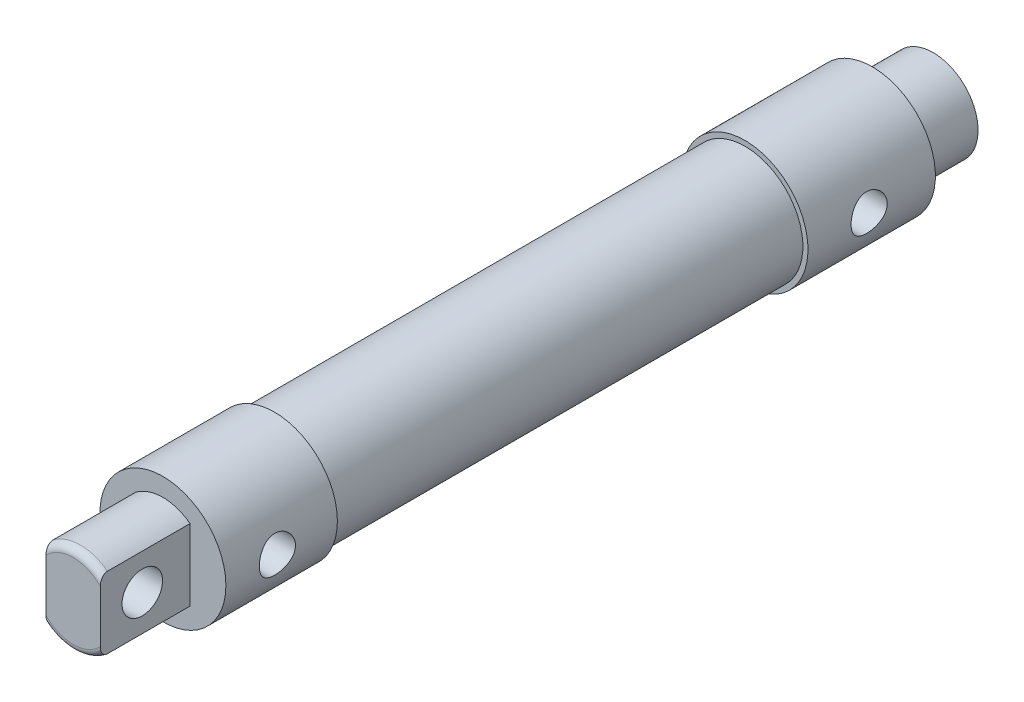
SolidWorks part; units mm, degrees
ref_plane "Front Plane" through (0, 0, 0) normal (0, 0, 1) x (1, 0, 0)
ref_plane "Top Plane" through (0, 0, 0) normal (0, 1, 0) x (1, 0, 0)
ref_plane "Right Plane" through (0, 0, 0) normal (1, 0, 0) x (0, 0, -1)
sketch "Sketch1" plane through (0, 0, 0) normal (0, 0, 1) x (1, 0, 0)
  circle A0 centre (0, 0) radius 10.16
  dimension "D1" = 20.32
extrude "Boss-Extrude1" add sketch "Sketch1" along normal blind 82.55
sketch "Sketch2" plane through (0, 0, 82.55) normal (0, 0, 1) x (1, 0, 0)
  circle A0 centre (0, 0) radius 11.049
  dimension "D1" = 22.098
extrude "Boss-Extrude2" add sketch "Sketch2" along normal blind 19.558 separate body
sketch "Sketch3" plane through (0, 0, 102.108) normal (0, 0, 1) x (1, 0, 0)
  line L0 (0, -7.874) -> (0, 7.874) construction
  line L1 (4.7625, -6.2704) -> (4.7625, 6.2704)
  line L2 (-4.7625, -6.2704) -> (-4.7625, 6.2704)
  line L3 (4.7625, -7.874) -> (4.7625, 7.874) construction
  line L4 (-4.7625, -7.874) -> (-4.7625, 7.874) construction
  arc A0 (4.7625, 6.2704) -> (-4.7625, 6.2704) centre (0, 0) ccw
  arc A1 (-4.7625, -6.2704) -> (4.7625, -6.2704) centre (0, 0) ccw
  dimension "D1" = 15.748
  dimension "D2" = 4.7625
  dimension "D3" = 4.7625
extrude "Boss-Extrude3" add sketch "Sketch3" along normal blind 15.748
sketch "Sketch4" plane through (4.7625, 0, 0) normal (1, 0, 0) x (0, 0, -1)
  line L0 (-117.856, 0) -> (-114.046, 0) construction
  line L1 (-117.856, -6.2704) -> (-117.856, 6.2704) construction
  circle A0 centre (-110.49, 0) radius 3.556
  dimension "D1" = 3.81
extrude "Cut-Extrude1" cut sketch "Sketch4" against normal up to next (9.525 mm away)
fillet "Fillet1" radius 1.27 2 edges at (0, 7.874, 117.856) (0, -7.874, 117.856)
sketch "Sketch5" plane through (0, 0, 0) normal (0, 0, -1) x (-1, 0, 0)
  circle A0 centre (0, 0) radius 11.049 construction
  circle A1 centre (0, 0) radius 11.049
extrude "Boss-Extrude4" add sketch "Sketch5" along normal blind 22.352
sketch "Sketch6" plane through (0, 0, -22.352) normal (0, 0, -1) x (-1, 0, 0)
  circle A0 centre (0, 0) radius 7.874
  dimension "D1" = 15.748
extrude "Boss-Extrude5" add sketch "Sketch6" along normal blind 10.668
sketch "Sketch7" plane through (0, 0, -33.02) normal (0, 0, -1) x (-1, 0, 0)
  circle A0 centre (0, 0) radius 3.175
  dimension "D1" = 6.35
extrude "Cut-Extrude2" cut sketch "Sketch7" against normal blind 124.968
ref_plane "Plane1" through (0, 0, 0) normal (1, 0, 0) x (0, 0, -1)
sketch "Sketch8" plane through (0, 0, 0) normal (1, 0, 0) x (0, 0, -1)
  circle A0 centre (-93.0761, 0) radius 3.175
  circle A1 centre (10.7398, 0) radius 3.175
  dimension "D1" = 6.35
  dimension "D2" = 6.35
extrude "Cut-Extrude3" cut sketch "Sketch8" along normal up to next
